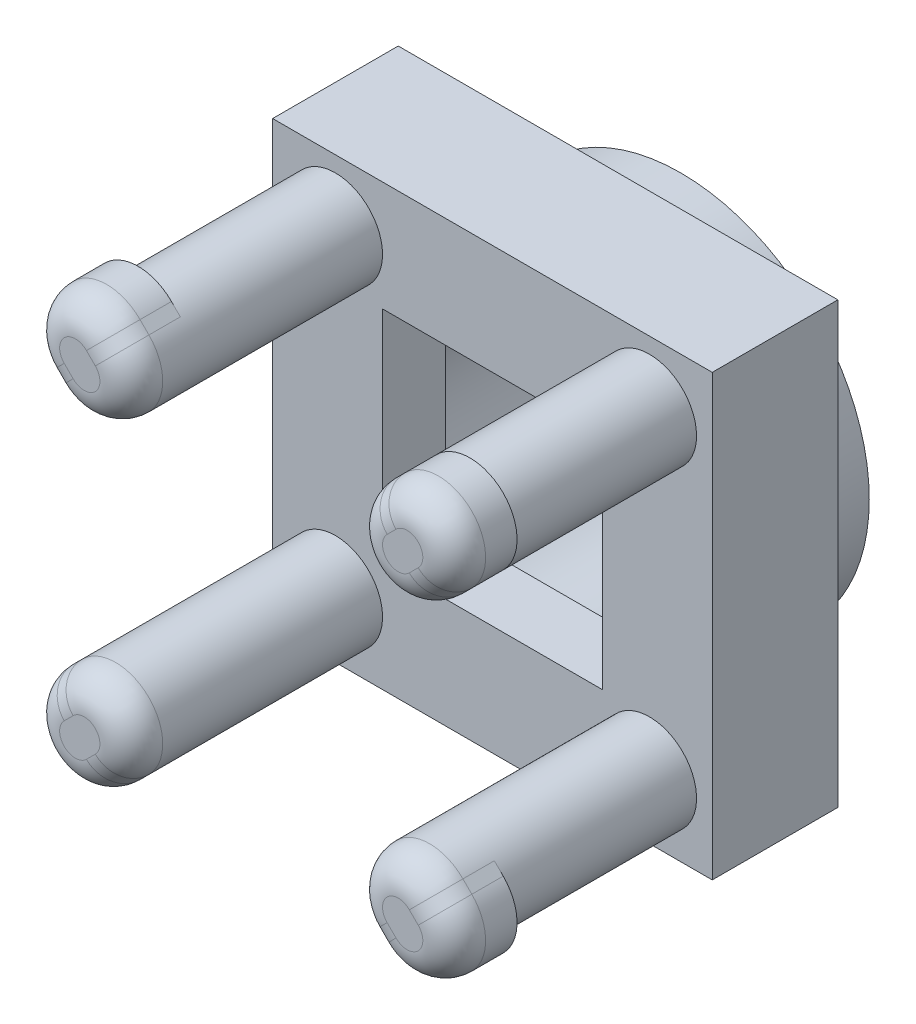
SolidWorks part; units mm, degrees
ref_plane "Plan de face" through (0, 0, 0) normal (0, 0, 1) x (1, 0, 0)
ref_plane "Plan de dessus" through (0, 0, 0) normal (0, 1, 0) x (1, 0, 0)
ref_plane "Plan de droite" through (0, 0, 0) normal (1, 0, 0) x (0, 0, -1)
sketch "Esquisse1" plane through (0, 0, 0) normal (0, 0, 1) x (1, 0, 0)
  line L1 (-3.5, 3.5) -> (3.5, 3.5)
  line L2 (-3.5, 3.5) -> (-3.5, -3.5)
  line L3 (-3.5, -3.5) -> (3.5, -3.5)
  line L4 (3.5, 3.5) -> (3.5, -3.5)
  line L5 (-3.5, 3.5) -> (3.5, -3.5) construction
  line L6 (-3.5, -3.5) -> (3.5, 3.5) construction
  point P0 (0, 0)
  dimension "D1" = 7
  dimension "D2" = 7
extrude "Boss.-Extru.1" add sketch "Esquisse1" along normal blind 2
sketch "Esquisse2" plane through (0, 0, 0) normal (0, 0, -1) x (-1, 0, 0)
  circle A0 centre (0, 0) radius 3
  circle A1 centre (0, 0) radius 2.032
  dimension "D1" = 6
extrude "Boss.-Extru.2" add sketch "Esquisse2" along normal blind 1
sketch "Esquisse3" plane through (-0.0084, -0.444, 2) normal (0, 0, 1) x (1, 0, 0)
  circle A0 centre (-2.4916, 2.944) radius 0.75
  dimension "D1" = 1.5
  dimension "D3" = 2.5
  dimension "D2" = 2.5
extrude "Boss.-Extru.3" add sketch "Esquisse3" along normal blind 3
sketch "Esquisse5" plane through (0, 0, 5) normal (0, 0, 1) x (1, 0, 0)
  line L0 (0, 0) -> (-2.5, 2.5) construction
  line L1 (-2.5, 2.5) -> (-2.6414, 2.6414) construction
  line L2 (-3.0303, 1.9697) -> (-3.1718, 2.1111)
  line L3 (-1.9697, 3.0303) -> (-2.1111, 3.1718)
  arc A0 (-3.0303, 1.9697) -> (-1.9697, 3.0303) centre (-2.5, 2.5) ccw
  arc A1 (-2.1111, 3.1718) -> (-3.1718, 2.1111) centre (-2.6414, 2.6414) ccw
  circle A2 centre (-2.5, 2.5) radius 0.75 construction
  point P4 (-2.5707, 2.5707)
  dimension "D1" = 0.2
extrude "Boss.-Extru.4" add sketch "Esquisse5" along normal blind 1
fillet "Congé1" radius 0.5 4 edges at (-1.9697, 1.9697, 6) (-3.101, 2.0404, 6) (-3.1718, 3.1718, 6) (-2.0404, 3.101, 6)
pattern_circular "Répétition circulaire2" count 4 over 360 about axis through (0, 0, 0) along (0, 0, 1) of "Boss.-Extru.3", "Boss.-Extru.4", "Congé1"
sketch "Esquisse6" plane through (0, 0, 2) normal (0, 0, 1) x (1, 0, 0)
  line L1 (-1.75, -1.75) -> (1.75, -1.75)
  line L2 (-1.75, -1.75) -> (-1.75, 1.75)
  line L3 (-1.75, 1.75) -> (1.75, 1.75)
  line L4 (1.75, -1.75) -> (1.75, 1.75)
  line L5 (-1.75, -1.75) -> (1.75, 1.75) construction
  line L6 (-1.75, 1.75) -> (1.75, -1.75) construction
  point P1 (0, 0)
  dimension "D1" = 3.5
  dimension "D2" = 3.5
extrude "Enlèv. mat.-Extru.1" cut sketch "Esquisse6" against normal blind 1
sketch "Esquisse7" plane through (0, 0, 0) normal (0, 0, -1) x (-1, 0, 0)
  circle A0 centre (0, 0) radius 2.032 construction
  circle A1 centre (0, 0) radius 2.032
extrude "Enlèv. mat.-Extru.2" cut sketch "Esquisse7" against normal blind 1
